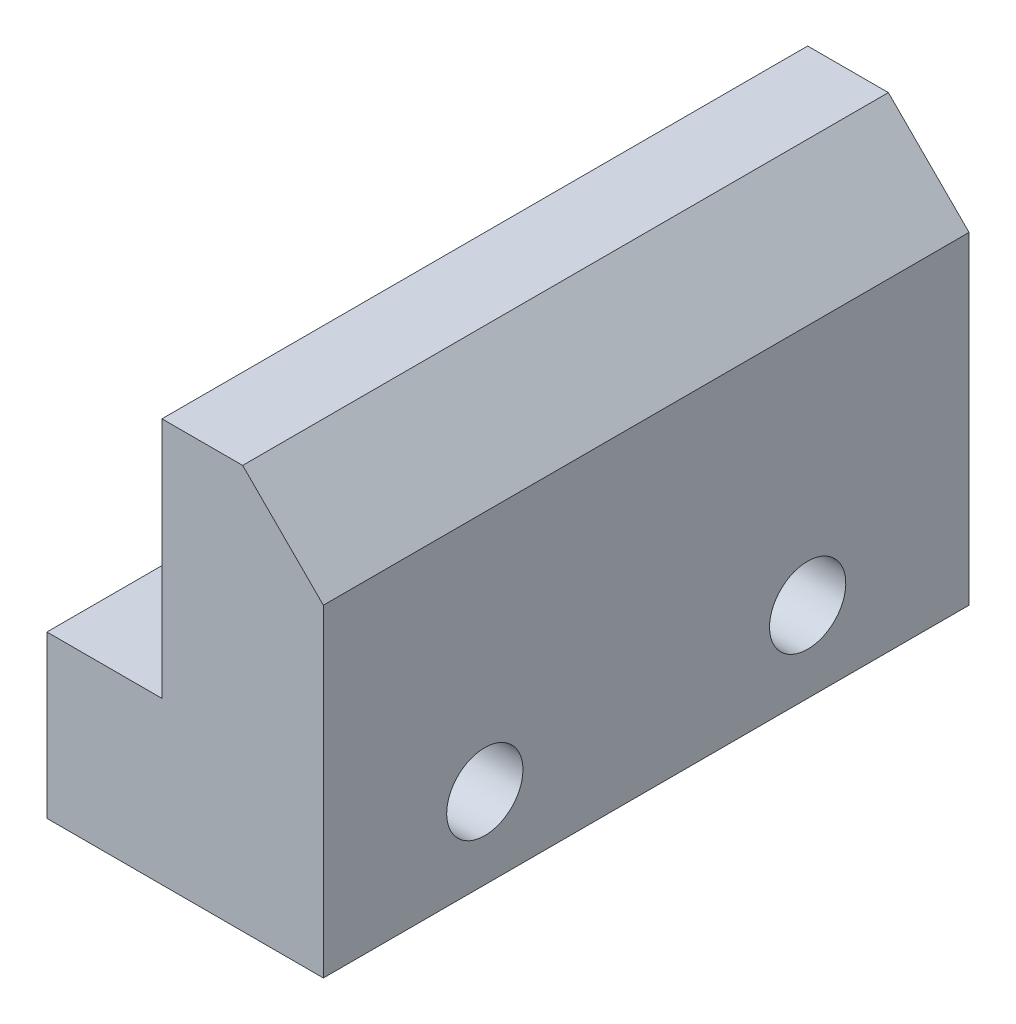
SolidWorks part; units mm, degrees
material "PETG"
ref_plane "Front Plane" through (0, 0, 0) normal (0, 0, 1) x (1, 0, 0)
ref_plane "Top Plane" through (0, 0, 0) normal (0, 1, 0) x (1, 0, 0)
ref_plane "Right Plane" through (0, 0, 0) normal (1, 0, 0) x (0, 0, -1)
sketch "Sketch1" plane through (0, 0, 0) normal (0, 0, 1) x (1, 0, 0)
  line L0 (18.1, 63.5) -> (43.5, 38.1)
  line L1 (0, -12.7) -> (43.5, -12.7)
  line L2 (0, -12.7) -> (0, 12.7)
  line L3 (0, 12.7) -> (18.1, 12.7)
  line L6 (18.1, 63.5) -> (18.1, 12.7)
  line L8 (43.5, 38.1) -> (43.5, -12.7)
  line L9 (18.1, 50.8) -> (30.8, 50.8)
  dimension "D1" = 25.4
  dimension "D2" = 43.5
  dimension "D3" = 50.8
  dimension "D4" = 25.4
  dimension "D5" = 25.4
extrude "Boss-Extrude1" add sketch "Sketch1" along normal mid plane 101.6 contours L9 L6 L3 L2 L1 L8 L0
sketch "Sketch2" plane through (43.5, 0, 0) normal (1, 0, 0) x (0, 0, -1)
  line L0 (-25.4, 0) -> (0, 0) construction
  line L1 (0, 0) -> (25.4, 0) construction
  line L2 (-50.8, 38.1) -> (-50.8, -12.7) construction
  circle A0 centre (-25.4, 0) radius 3.25
  circle A1 centre (25.4, 0) radius 3.25
  dimension "D1" = 25.4
  dimension "D2" = 6.5
extrude "Cut-Extrude1" cut sketch "Sketch2" against normal through all
sketch "Sketch3" plane through (43.5, 0, 0) normal (1, 0, 0) x (0, 0, -1)
  circle A0 centre (-25.4, 0) radius 6
  circle A1 centre (25.4, 0) radius 6
  dimension "D1" = 12
extrude "Cut-Extrude2" cut sketch "Sketch3" against normal offset from surface (33.5 mm away) 10 up to face at (0, 3.25, 25.4)
